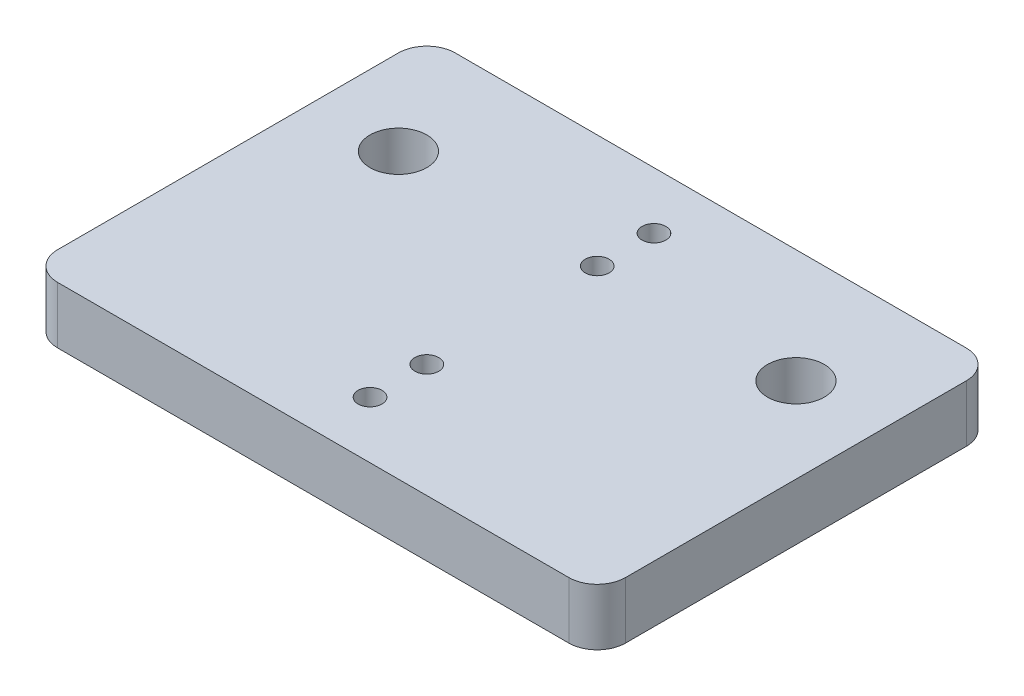
SolidWorks part; units mm, degrees
material "6061 Alloy"
ref_plane "Front Plane" through (0, 0, 0) normal (0, 0, 1) x (1, 0, 0)
ref_plane "Top Plane" through (0, 0, 0) normal (0, 1, 0) x (1, 0, 0)
ref_plane "Right Plane" through (0, 0, 0) normal (1, 0, 0) x (0, 0, -1)
sketch "Sketch2" plane through (0, 0, 0) normal (0, 1, 0) x (1, 0, 0)
  line L0 (0, 39.1529) -> (0, 26.4529) construction
  line L1 (-63.5, 39.1529) -> (63.5, 39.1529)
  line L2 (-63.5, 39.1529) -> (-63.5, -49.7471)
  line L3 (-63.5, -49.7471) -> (63.5, -49.7471)
  line L4 (63.5, -49.7471) -> (63.5, 39.1529)
  line L7 (-6.35, 39.1529) -> (6.35, 39.1529)
  line L8 (-6.35, 39.1529) -> (-6.35, 1.0529)
  line L9 (-6.35, 1.0529) -> (6.35, 1.0529)
  line L10 (6.35, 39.1529) -> (6.35, 1.0529)
  line L11 (-63.5, 1.0529) -> (63.5, 1.0529)
  line L12 (-63.5, 1.0529) -> (-63.5, -11.6471)
  line L13 (-63.5, -11.6471) -> (63.5, -11.6471)
  line L14 (63.5, 1.0529) -> (63.5, -11.6471)
  line L15 (-6.35, -11.6471) -> (6.35, -11.6471)
  line L16 (-6.35, -11.6471) -> (-6.35, -49.7471)
  line L17 (-6.35, -49.7471) -> (6.35, -49.7471)
  line L18 (6.35, -11.6471) -> (6.35, -49.7471)
  line L19 (0, 26.4529) -> (0, 13.7529) construction
  line L20 (0, 13.7529) -> (0, 1.0529) construction
  line L22 (0, -11.6471) -> (0, -24.3471) construction
  line L23 (0, -24.3471) -> (0, -37.0471) construction
  line L24 (0, -37.0471) -> (0, -49.7471) construction
  circle A0 centre (-44.45, 13.7529) radius 6.35
  circle A1 centre (44.45, 13.7529) radius 6.35
  circle A2 centre (0, -37.0471) radius 2.667
  circle A3 centre (0, -24.3471) radius 2.667
  circle A4 centre (0, 13.7529) radius 2.667
  circle A5 centre (0, 26.4529) radius 2.667
  point P0 (0, 0)
  dimension "D3" = 12.7
  dimension "D4" = 127
  dimension "D9" = 5.334
  dimension "D1" = 19.05
  dimension "D5" = 19.05
  dimension "D2" = 12.7
  dimension "D10" = 12.7
  dimension "D6" = 12.7
  dimension "D7" = 25.4
  dimension "D8" = 12.7
extrude "Boss-Extrude1" add sketch "Sketch2" along normal blind 12.7
fillet "Fillet1" radius 6.35 4 edges at (-63.5, 6.35, -39.1529) (63.5, 6.35, -39.1529) (63.5, 6.35, 49.7471) (-63.5, 6.35, 49.7471)
